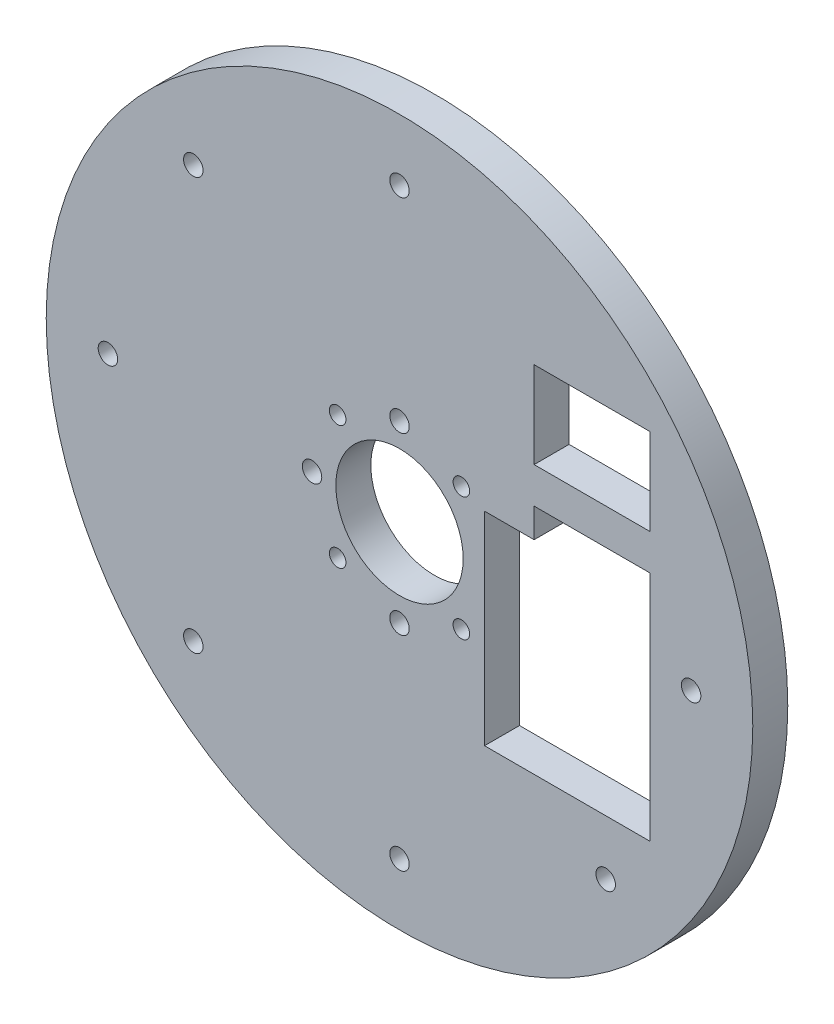
SolidWorks part; units mm, degrees
material "Balsa"
ref_plane "Front Plane" through (0, 0, 0) normal (0, 0, 1) x (1, 0, 0)
ref_plane "Top Plane" through (0, 0, 0) normal (0, 1, 0) x (1, 0, 0)
ref_plane "Right Plane" through (0, 0, 0) normal (1, 0, 0) x (0, 0, -1)
sketch "Sketch1" plane through (0, 0, 0) normal (0, 0, 1) x (1, 0, 0)
  circle A2 centre (0, 0) radius 60.5
  circle A3 centre (0, 0) radius 11
  circle A4 centre (0, 0) radius 15 construction
  circle A6 centre (0, 0) radius 50 construction
  circle A27 centre (0, -15) radius 1.75
  circle A28 centre (10.6066, -10.6066) radius 1.5
  circle A30 centre (0, -50) radius 1.75
  circle A31 centre (-15, 0) radius 1.75
  circle A32 centre (-10.6066, -10.6066) radius 1.5
  circle A33 centre (0, 15) radius 1.75
  circle A34 centre (-10.6066, 10.6066) radius 1.5
  circle A35 centre (15, 0) radius 1.75 construction
  circle A36 centre (10.6066, 10.6066) radius 1.5
  circle A38 centre (-35.3553, -35.3553) radius 1.75
  circle A40 centre (-50, 0) radius 1.75
  circle A42 centre (-35.3553, 35.3553) radius 1.75
  circle A44 centre (0, 50) radius 1.75
  circle A46 centre (35.3553, 35.3553) radius 1.75 construction
  circle A48 centre (50, 0) radius 1.75
  circle A50 centre (35.3553, -35.3553) radius 1.75
  dimension "D1" = 121
  dimension "D6" = 100
  dimension "D8" = 30
  dimension "D15" = 3.5
  dimension "D17" = 3.5
  dimension "D18" = 3
  dimension "D3" = 22
  dimension "D19" = 45
  dimension "D20" = 4
  dimension "D21" = 8
extrude "Boss-Extrude1" add sketch "Sketch1" along normal blind 6
sketch "Sketch2" plane through (0, 0, 6) normal (0, 0, 1) x (1, 0, 0)
  line L0 (23, 14) -> (43, 14)
  line L1 (23, 20) -> (43, 20)
  line L2 (23, 20) -> (23, 35)
  line L3 (23, 35) -> (43, 35)
  line L4 (43, 20) -> (43, 35)
  line L5 (43, 14) -> (43, -26)
  line L6 (43, -26) -> (14.5, -26)
  line L7 (14.5, -26) -> (14.5, 9)
  line L8 (14.5, 9) -> (23, 9)
  line L9 (23, 9) -> (23, 14)
  dimension "D1" = 20
  dimension "D2" = 8.5
  dimension "D3" = 6
  dimension "D4" = 5
  dimension "D5" = 15
  dimension "D6" = 40
  dimension "D7" = 35
  dimension "D8" = 23
extrude "Cut-Extrude1" cut sketch "Sketch2" against normal through all
other "Move Face1" face at (23, 27.5, 3) face at (11, 0, 6) face at (60.5, 0, 6) face at (1.75, -15, 6) face at (12.1066, -10.6066, 6) face at (1.75, -50, 6) face at (-13.25, 0, 6) face at (-9.1066, -10.6066, 6) face at (1.75, 15, 6) face at (-9.1066, 10.6066, 6) face at (12.1066, 10.6066, 6) face at (-33.6053, -35.3553, 6) face at (-48.25, 0, 6) face at (-33.6053, 35.3553, 6) face at (1.75, 50, 6) face at (51.75, 0, 6) face at (37.1053, -35.3553, 6) face at (18.75, 9, 3) face at (14.5, -8.5, 3) face at (28.75, -26, 3) face at (43, -6, 3) face at (33, 14, 3) face at (23, 11.5, 3) face at (33, 20, 3) face at (43, 27.5, 3) face at (33, 35, 3) parameters "D1"=0.08
